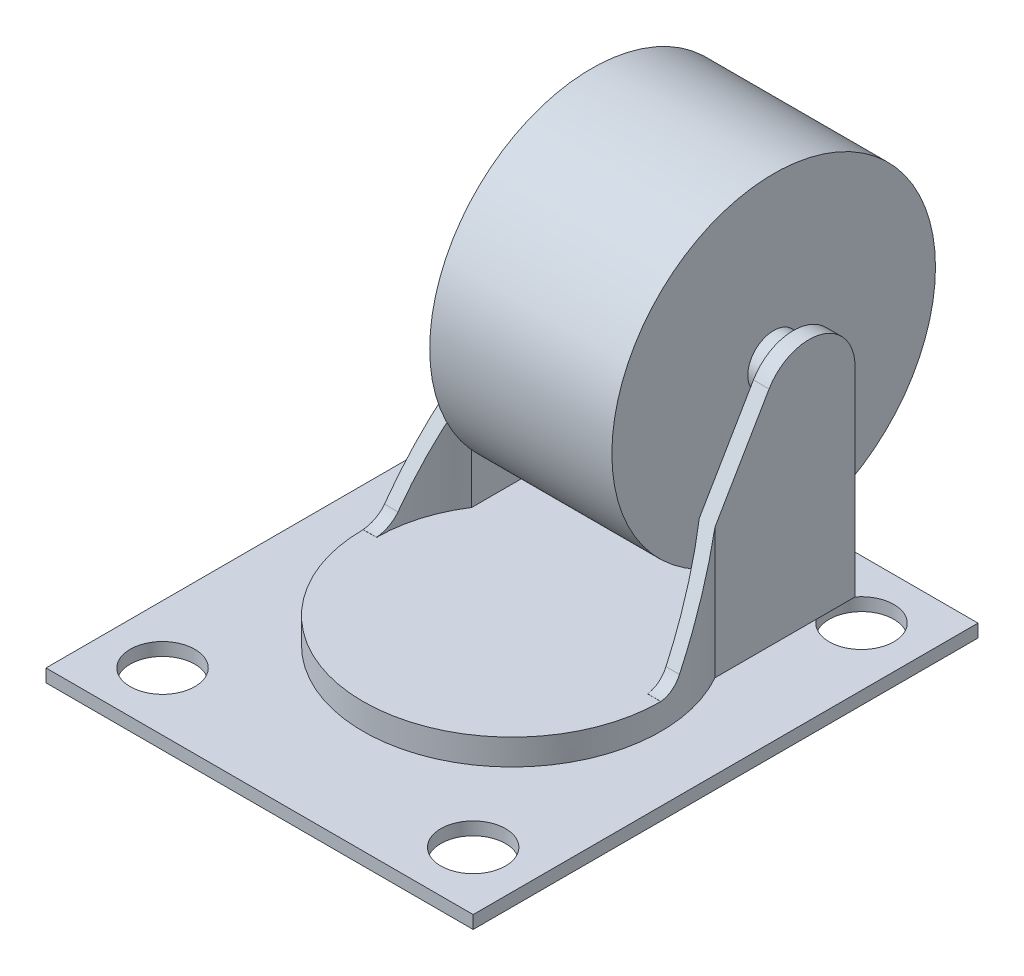
SolidWorks part; units mm, degrees
ref_plane "Front Plane" through (0, 0, 0) normal (0, 0, 1) x (1, 0, 0)
ref_plane "Top Plane" through (0, 0, 0) normal (0, 1, 0) x (1, 0, 0)
ref_plane "Right Plane" through (0, 0, 0) normal (1, 0, 0) x (0, 0, -1)
sketch "Sketch1" plane through (0, 0, 0) normal (0, 1, 0) x (1, 0, 0)
  line L0 (-16.5, -19.5) -> (-16.5, 19.5)
  line L1 (-12, -15) -> (-9.5, -15)
  line L2 (-12, -15) -> (-12, -12.5)
  line L3 (-12, 15) -> (-9.5, 15)
  line L4 (12, -15) -> (12, -12.5)
  line L5 (-12, -15) -> (-10.4383, -13.0478) construction
  line L6 (-12, 15) -> (-10.4383, 13.0478) construction
  line L7 (-16.5, 19.5) -> (16.5, 19.5)
  line L8 (16.5, -19.5) -> (16.5, 19.5)
  line L9 (-16.5, -19.5) -> (16.5, -19.5)
  line L10 (-12, 12.5) -> (-12, 15)
  line L11 (-12, -15) -> (-12, 15) construction
  line L12 (10.4383, -13.0478) -> (12, -15) construction
  line L13 (9.5, 15) -> (12, 15)
  line L14 (-12, 15) -> (12, 15) construction
  line L15 (10.4383, 13.0478) -> (12, 15) construction
  line L16 (12, 12.5) -> (12, 15)
  line L17 (12, -15) -> (12, 15) construction
  line L18 (9.5, -15) -> (12, -15)
  line L19 (-12, -15) -> (12, -15) construction
  circle A0 centre (12, 15) radius 2.5
  circle A1 centre (-12, 15) radius 2.5
  circle A2 centre (-12, -15) radius 2.5
  circle A3 centre (12, -15) radius 2.5
  point P0 (0, 0)
  dimension "D4" = 2
  dimension "D1" = 30
  dimension "D2" = 24
  dimension "D3" = 4.5
  dimension "D5" = 2
extrude "Boss-Extrude1" add sketch "Sketch1" along normal blind 1 contours L0 L9 L8 L7 A3 A2 A1 A0
sketch "Sketch2" plane through (0, 1, 0) normal (0, 1, 0) x (1, 0, 0)
  line L2 (10, 5.6789) -> (10, 16.5)
  line L3 (10, 16.5) -> (-10, 16.5)
  line L4 (-10, 5.6789) -> (-10, 16.5)
  arc A0 (-10, 5.6789) -> (10, 5.6789) centre (0, 0) ccw
  dimension "D1" = 20
extrude "Boss-Extrude2" add sketch "Sketch2" along normal blind 2
ref_plane "Plane1" through (0, 20, 0) normal (0, 1, 0) x (1, 0, 0)
sketch "Sketch3" plane through (0, 20, 0) normal (0, 1, 0) x (1, 0, 0)
  line L0 (-10.4664, 0) -> (-11.5, 0)
  line L1 (-10, 16.5) -> (-8.7917, 16.5)
  line L2 (-10, 16.5) -> (-10, 5.6789)
  line L4 (-8.7917, 16.5) -> (-8.7917, 5.6789)
  line L5 (0, 0) -> (0, 23.5238) construction
  line L6 (8.7917, 16.5) -> (8.7917, 5.6789)
  line L7 (10, 16.5) -> (10, 5.6789)
  line L8 (10, 16.5) -> (8.7917, 16.5)
  line L9 (10.4664, 0) -> (11.5, 0)
  arc A0 (-8.7917, 5.6789) -> (-10.4664, 0) centre (0, 0) ccw
  arc A1 (-10, 5.6789) -> (10, 5.6789) centre (0, 0) ccw construction
  arc A2 (-11.5, 0) -> (-10, 5.6789) centre (0, 0) cw
  arc A3 (11.5, 0) -> (10, 5.6789) centre (0, 0) ccw
  arc A4 (8.7917, 5.6789) -> (10.4664, 0) centre (0, 0) cw
extrude "Boss-Extrude3" add sketch "Sketch3" against normal up to surface (17 mm away) up to face at (0, 3, -6.7947)
sketch "Sketch4" plane through (10, 0, 0) normal (1, 0, 0) x (0, 0, -1)
  line L1 (-2.6138, 3) -> (-0.1851, 3)
  line L2 (0, 3) -> (-11.5, 3) construction
  line L3 (1.5419, 3.9914) -> (9.8593, 18.2336)
  line L4 (16.5, 16.4365) -> (17.784, 20)
  line L5 (12.65, 20) -> (-12.65, 20) construction
  line L6 (17.784, 20) -> (0.5504, 24.1965)
  line L7 (0.5504, 24.1965) -> (-11.3818, 8.6047)
  line L8 (-11.3818, 8.6047) -> (-2.6138, 3)
  arc A0 (16.5, 16.4365) -> (9.8593, 18.2336) centre (12.9365, 16.4365) ccw
  arc A1 (-0.1851, 3) -> (1.5419, 3.9914) centre (-0.1851, 5) ccw
  dimension "D1" = 2
extrude "Cut-Extrude1" cut sketch "Sketch4" against normal through all both and the other way through all contours A0 L3 A1 L1 L8 L7 L6 L4
ref_plane "Plane2" through (0, 17, 0) normal (0, 1, 0) x (1, 0, 0)
sketch "Sketch5" plane through (0, 17, 0) normal (0, 1, 0) x (1, 0, 0)
  line L0 (8.7917, 9.8593) -> (8.7917, 16.5)
  line L1 (10, 16.5) -> (-10, 16.5) construction
  line L2 (8.7917, 16.5) -> (8.7917, 9.8593) construction
  line L3 (8.7917, 16.5) -> (8.7917, 13.1796)
  line L4 (8.7917, 13.1796) -> (-8.7917, 13.1796)
  line L5 (-8.7917, 9.8593) -> (-8.7917, 16.5) construction
  line L6 (-8.7917, 13.1796) -> (-8.7917, 11.1796)
  line L7 (-8.7917, 16.5) -> (-8.7917, 5.6789) construction
  line L8 (-8.7917, 11.1796) -> (-7.0351, 11.1796)
  line L9 (-7.0351, 11.1796) -> (-7.0351, 0.6796)
  line L10 (0, 13.1796) -> (0, -7.8969) construction
  line L11 (7.0351, 11.1796) -> (7.0351, 0.6796)
  line L12 (8.7917, 11.1796) -> (7.0351, 11.1796)
  line L13 (8.7917, 13.1796) -> (8.7917, 11.1796)
  line L14 (7.0351, 0.6796) -> (-7.0351, 0.6796)
  dimension "D1" = 2
  dimension "D2" = 12.5
revolve "Revolve1" add sketch "Sketch5" angle 360 about L4
